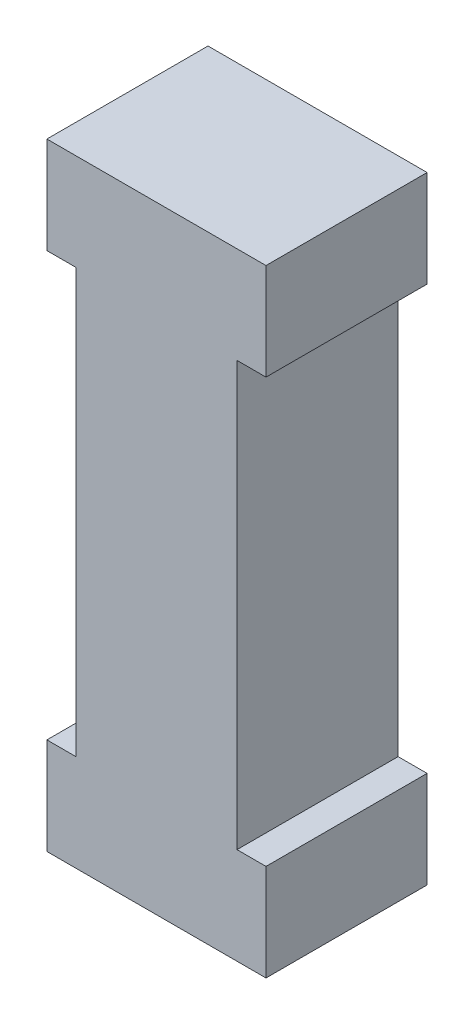
SolidWorks part; units mm, degrees
ref_plane "Front Plane" through (0, 0, 0) normal (0, 0, 1) x (1, 0, 0)
ref_plane "Top Plane" through (0, 0, 0) normal (0, 1, 0) x (1, 0, 0)
ref_plane "Right Plane" through (0, 0, 0) normal (1, 0, 0) x (0, 0, -1)
sketch "Sketch1" plane through (0, 0, 0) normal (0, 0, 1) x (1, 0, 0)
  line L0 (-2.5, -3) -> (-2.5, 16.15) construction
  line L2 (0, 0) -> (0, 13.15)
  line L4 (-5, 0) -> (-5, 13.15)
  line L5 (-5.9, 16.15) -> (0.9, 16.15)
  line L6 (-5.9, 16.15) -> (-5.9, 13.15)
  line L7 (-5.9, 13.15) -> (-5, 13.15)
  line L8 (0.9, 16.15) -> (0.9, 13.15)
  line L9 (-5.9, -3) -> (0.9, -3)
  line L10 (-5.9, -3) -> (-5.9, 0)
  line L11 (-5.9, 0) -> (-5, 0)
  line L12 (0.9, -3) -> (0.9, 0)
  line L13 (0, 0) -> (0.9, 0)
  line L14 (0, 13.15) -> (0.9, 13.15)
  point P15 (-5.9, 0)
  point P16 (-2.5, -5.0908)
  dimension "D1" = 6.8
  dimension "D2" = 19.15
  dimension "D3" = 3
  dimension "D4" = 2.5
  dimension "D5" = 5
extrude "Boss-Extrude1" add sketch "Sketch1" along normal blind 5
